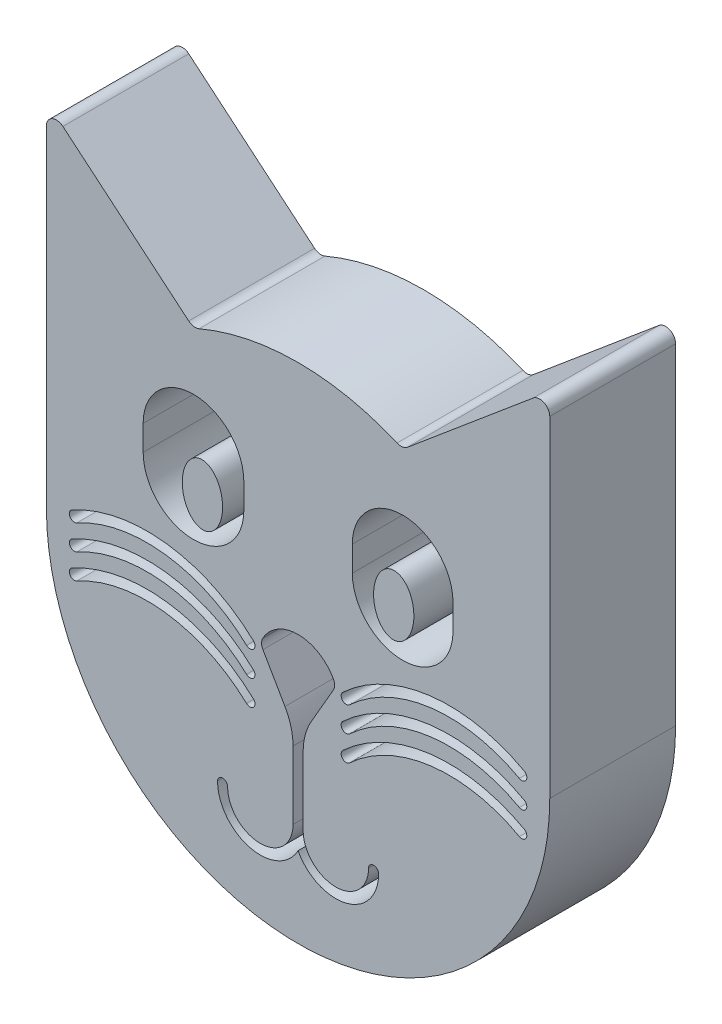
SolidWorks part; units mm, degrees
ref_plane "Front Plane" through (0, 0, 0) normal (0, 0, 1) x (1, 0, 0)
ref_plane "Top Plane" through (0, 0, 0) normal (0, 1, 0) x (1, 0, 0)
ref_plane "Right Plane" through (0, 0, 0) normal (1, 0, 0) x (0, 0, -1)
sketch "Sketch1" plane through (0, 0, 0) normal (0, 0, 1) x (1, 0, 0)
  line L1 (-25.4, 25.4) -> (25.4, 25.4)
  line L2 (-25.4, 25.4) -> (-25.4, -25.4)
  line L3 (-25.4, -25.4) -> (25.4, -25.4)
  line L4 (25.4, 25.4) -> (25.4, -25.4)
  line L5 (-25.4, 25.4) -> (25.4, -25.4) construction
  line L6 (-25.4, -25.4) -> (25.4, 25.4) construction
  point P0 (0, 0)
  dimension "D1" = 50.8
  dimension "D2" = 50.8
extrude "Boss-Extrude1" add sketch "Sketch1" along normal blind 6.35
sketch "Sketch4" plane through (0, 0, 6.35) normal (0, 0, 1) x (1, 0, 0)
  line L0 (1.7402, -3.6573) -> (1.7402, -7.4673)
  line L1 (2.2482, -3.6573) -> (2.2482, -7.4673)
  line L2 (-10.7058, 17.9327) -> (-10.7058, 0.1527)
  line L3 (-3.2831, 6.2845) -> (-3.2831, 5.0145) construction
  line L4 (-3.2831, 11.7044) -> (-10.7058, 17.9327)
  line L5 (1.9942, 12.8527) -> (1.9942, -3.6486) construction
  line L6 (-0.7431, 6.2845) -> (-0.7431, 5.0145)
  line L7 (14.6942, 17.9327) -> (14.6942, 0.1527)
  line L8 (7.2715, 11.7044) -> (14.6942, 17.9327)
  line L9 (-5.8231, 6.2845) -> (-5.8231, 5.0145)
  line L10 (7.2715, 6.2845) -> (7.2715, 5.0145) construction
  line L11 (4.7315, 6.2845) -> (4.7315, 5.0145)
  line L12 (9.8115, 6.2845) -> (9.8115, 5.0145)
  line L13 (2.1212, -3.4373) -> (3.8992, -0.3577)
  line L14 (1.8672, -3.4373) -> (0.0892, -0.3577)
  line L15 (1.9942, -3.6573) -> (1.9942, -7.4673)
  line L18 (1.9942, -8.4833) -> (1.9942, -12.5473) construction
  arc A0 (7.2715, 11.7044) -> (-3.2831, 11.7044) centre (1.9942, 0.1527) ccw
  arc A1 (-10.7058, 0.1527) -> (14.6942, 0.1527) centre (1.9942, 0.1527) ccw
  arc A2 (-0.7431, 6.2845) -> (-5.8231, 6.2845) centre (-3.2831, 6.2845) ccw
  arc A3 (-5.8231, 5.0145) -> (-0.7431, 5.0145) centre (-3.2831, 5.0145) ccw
  arc A4 (4.7315, 6.2845) -> (9.8115, 6.2845) centre (7.2715, 6.2845) cw
  arc A5 (9.8115, 5.0145) -> (4.7315, 5.0145) centre (7.2715, 5.0145) cw
  arc A6 (0.0892, -0.3577) -> (3.8992, -0.3577) centre (1.9942, -1.0648) cw
  arc A7 (-3.2831, 11.7044) -> (-5.6258, 10.3127) centre (1.9942, 0.1527) ccw
  arc A8 (-10.7058, 0.1527) -> (-9.7763, 4.9218) centre (1.9942, 0.1527) cw
  arc A9 (7.2715, 11.7044) -> (9.6142, 10.3127) centre (1.9942, 0.1527) cw
  arc A10 (14.6942, 0.1527) -> (13.7648, 4.9218) centre (1.9942, 0.1527) ccw
  arc A11 (2.1212, -3.4373) -> (2.2482, -3.6573) centre (1.9942, -3.6573) cw
  arc A12 (4.2491, -1.704) -> (13.4046, -0.5656) centre (9.6142, -7.4673) cw
  arc A14 (4.5952, -2.0758) -> (13.16, -1.0108) centre (9.6142, -7.4673) cw
  arc A15 (1.7402, -7.4673) -> (-1.5618, -7.4673) centre (0.0892, -7.4673) cw
  arc A16 (1.9942, -8.4833) -> (6.0582, -7.4673) centre (3.8992, -7.4673) ccw
  arc A17 (4.5952, -0.8058) -> (13.16, 0.2592) centre (9.6142, -6.1973) cw
  arc A18 (1.9942, -8.4833) -> (-2.0698, -7.4673) centre (0.0892, -7.4673) cw
  arc A19 (2.2482, -7.4673) -> (5.5502, -7.4673) centre (3.8992, -7.4673) ccw
  arc A20 (4.2491, -0.434) -> (13.4046, 0.7044) centre (9.6142, -6.1973) cw
  arc A21 (4.5952, -2.0758) -> (4.2491, -1.704) centre (4.4221, -1.8899) cw
  arc A22 (-1.5618, -7.4673) -> (-2.0698, -7.4673) centre (-1.8158, -7.4673) ccw
  arc A23 (1.7402, -3.6573) -> (1.8672, -3.4373) centre (1.9942, -3.6573) cw
  arc A24 (13.16, -1.0108) -> (13.4046, -0.5656) centre (13.2823, -0.7882) ccw
  arc A25 (4.2491, -2.974) -> (13.4046, -1.8356) centre (9.6142, -8.7373) cw
  arc A26 (6.0582, -7.4673) -> (5.5502, -7.4673) centre (5.8042, -7.4673) ccw
  arc A27 (4.5952, -0.8058) -> (4.2491, -0.434) centre (4.4221, -0.6199) cw
  arc A28 (13.16, 0.2592) -> (13.4046, 0.7044) centre (13.2823, 0.4818) ccw
  arc A29 (4.5952, -3.3458) -> (13.16, -2.2808) centre (9.6142, -8.7373) cw
  arc A30 (4.5952, -3.3458) -> (4.2491, -2.974) centre (4.4221, -3.1599) cw
  arc A31 (13.16, -2.2808) -> (13.4046, -1.8356) centre (13.2823, -2.0582) ccw
  arc A32 (-9.1716, -1.0108) -> (-9.4161, -0.5656) centre (-9.2938, -0.7882) cw
  arc A33 (-9.1716, -2.2808) -> (-9.4161, -1.8356) centre (-9.2938, -2.0582) cw
  arc A34 (-0.6068, -3.3458) -> (-9.1716, -2.2808) centre (-5.6258, -8.7373) ccw
  arc A35 (-0.2606, -2.974) -> (-9.4161, -1.8356) centre (-5.6258, -8.7373) ccw
  arc A36 (-0.6068, -3.3458) -> (-0.2606, -2.974) centre (-0.4337, -3.1599) ccw
  arc A37 (-0.6068, -2.0758) -> (-0.2606, -1.704) centre (-0.4337, -1.8899) ccw
  arc A38 (-0.6068, -2.0758) -> (-9.1716, -1.0108) centre (-5.6258, -7.4673) ccw
  arc A39 (-0.2606, -1.704) -> (-9.4161, -0.5656) centre (-5.6258, -7.4673) ccw
  arc A40 (-9.1716, 0.2592) -> (-9.4161, 0.7044) centre (-9.2938, 0.4818) cw
  arc A41 (-0.6068, -0.8058) -> (-0.2606, -0.434) centre (-0.4337, -0.6199) ccw
  arc A42 (-0.6068, -0.8058) -> (-9.1716, 0.2592) centre (-5.6258, -6.1973) ccw
  arc A43 (-0.2606, -0.434) -> (-9.4161, 0.7044) centre (-5.6258, -6.1973) ccw
  ellipse E0 centre (-2.8318, 4.6608) end of major axis (-2.7908, 3.1373) minor radius 1.016
  ellipse E1 centre (6.8202, 4.6608) end of major axis (6.7793, 3.1373) minor radius 1.016
  point P15 (-3.2831, 5.6495)
  point P28 (7.2715, 5.6495)
  dimension "D1" = 25.4
  dimension "D7" = 1.27
  dimension "D6" = 2.54
  dimension "D18" = 2.032
  dimension "D19" = 5.08
  dimension "D22" = 7.62
  dimension "D23" = 3
  dimension "D28" = 0.254
  dimension "D21" = 11.2118
  dimension "D4" = 50
  dimension "D5" = 17.78
  dimension "D8" = 7.62
  dimension "D9" = 6.604
  dimension "D10" = 4.826
  dimension "D11" = 2.032
  dimension "D12" = 3.048
  dimension "D13" = 1.016
  dimension "D14" = 30
  dimension "D15" = 3.81
  dimension "D16" = 30
  dimension "D17" = 3.81
  dimension "D20" = 3.81
  dimension "D29" = 0.254
extrude "Cut-Extrude7" cut sketch "Sketch4" against normal blind 6.35
fillet "Fillet4" radius 0.508 6 edges at (0.0892, -0.3577, 3.175) (3.8992, -0.3577, 3.175) (14.6942, 17.9327, 3.175) (7.2715, 11.7044, 3.175) (-3.2831, 11.7044, 3.175) (-10.7058, 17.9327, 3.175)
fillet "Fillet5" radius 3.048 2 edges at (2.1212, -3.4373, 3.175) (1.8672, -3.4373, 3.175)
